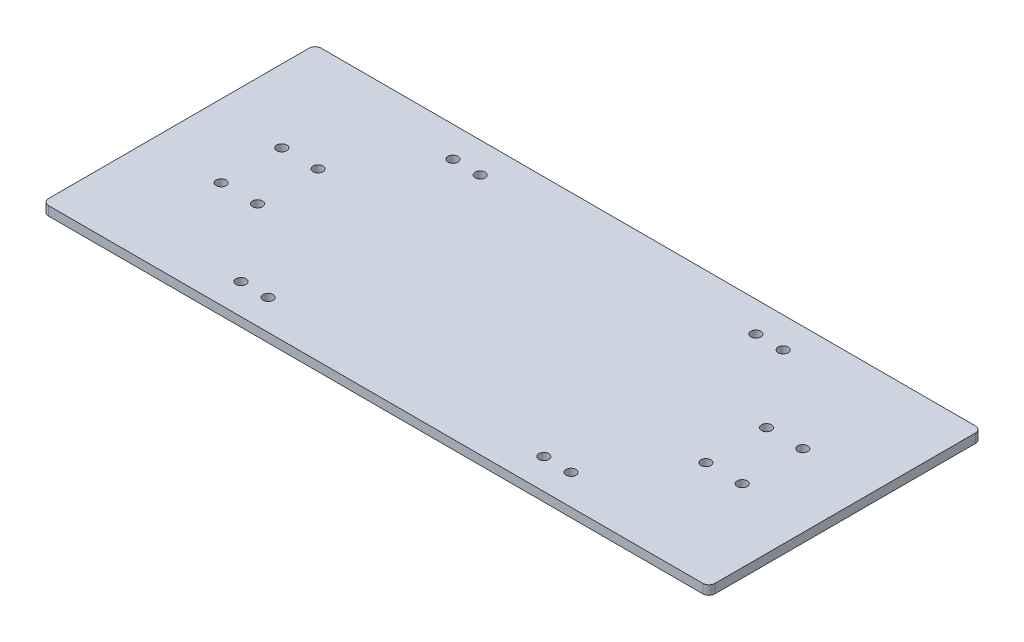
SolidWorks part; units mm, degrees
ref_plane "前视基准面" through (0, 0, 0) normal (0, 0, 1) x (1, 0, 0)
ref_plane "上视基准面" through (0, 0, 0) normal (0, 1, 0) x (1, 0, 0)
ref_plane "右视基准面" through (0, 0, 0) normal (1, 0, 0) x (0, 0, -1)
sketch "草图1" plane through (0, 0, 0) normal (0, 1, 0) x (1, 0, 0)
  line L1 (-110, -45) -> (110, -45)
  line L2 (-110, -45) -> (-110, 45)
  line L3 (-110, 45) -> (110, 45)
  line L4 (110, -45) -> (110, 45)
  line L5 (-110, -45) -> (110, 45) construction
  line L6 (-110, 45) -> (110, -45) construction
  point P0 (0, 0)
  dimension "D1" = 90
  dimension "D2" = 220
extrude "凸台-拉伸1" add sketch "草图1" along normal blind 3
sketch "草图3" plane through (0, 3, 0) normal (0, 1, 0) x (1, 0, 0)
  line L0 (-36.2529, 0) -> (70.3375, 0) construction
  line L1 (23.5, -7.5) -> (43.5, -7.5) construction
  line L2 (23.5, -7.5) -> (23.5, 7.5) construction
  line L3 (23.5, 7.5) -> (43.5, 7.5) construction
  line L4 (43.5, -7.5) -> (43.5, 7.5) construction
  line L5 (23.5, -7.5) -> (43.5, 7.5) construction
  line L6 (23.5, 7.5) -> (43.5, -7.5) construction
  circle A0 centre (43.5, 7.5) radius 1.65
  circle A1 centre (23.5, 7.5) radius 1.65
  circle A2 centre (23.5, -7.5) radius 1.65
  circle A3 centre (43.5, -7.5) radius 1.65
  point P0 (-1.7994, 0)
  point P12 (33.5, 0)
  dimension "D3" = 3.3
  dimension "D4" = 3.3
  dimension "D5" = 3.3
  dimension "D6" = 3.3
  dimension "D1" = 15
  dimension "D2" = 20
  dimension "D7" = 33.5
extrude "切除-拉伸1" [suppressed] cut sketch "草图3" against normal blind 3
sketch "草图4" plane through (0, 3, 0) normal (0, 1, 0) x (1, 0, 0)
  line L0 (0, 51.7691) -> (0, -54.2842) construction
  line L6 (-50, -35) -> (50, -35) construction
  line L7 (-50, -35) -> (-50, 35) construction
  line L8 (-50, 35) -> (50, 35) construction
  line L9 (50, -35) -> (50, 35) construction
  line L10 (-50, -35) -> (50, 35) construction
  line L11 (-50, 35) -> (50, -35) construction
  circle A0 centre (54.5, 35) radius 1.65
  circle A1 centre (45.5, 35) radius 1.65
  circle A3 centre (-54.5, 35) radius 1.65
  circle A4 centre (-45.5, 35) radius 1.65
  point P3 (0, 0)
  dimension "D3" = 3.3
  dimension "D4" = 3.3
  dimension "D5" = 9
  dimension "D6" = 4.5
  dimension "D1" = 100
  dimension "D2" = 70
extrude "切除-拉伸2" cut sketch "草图4" against normal blind 3
mirror "镜向1" about plane through (0, 0, 0) normal (0, 0, 1) of "切除-拉伸2"
mirror "镜向2" [suppressed] about plane through (0, 0, 0) normal (1, 0, 0)
sketch "草图5" plane through (0, 3, 0) normal (0, 1, 0) x (1, 0, 0)
  line L0 (-129.3257, 0) -> (142.7422, 0) construction
  line L1 (0, 64.113) -> (0, -80.8286) construction
  line L3 (74, -10) -> (86, -10) construction
  line L4 (74, -10) -> (74, 10) construction
  line L5 (74, 10) -> (86, 10) construction
  line L6 (86, -10) -> (86, 10) construction
  line L7 (74, -10) -> (86, 10) construction
  line L8 (74, 10) -> (86, -10) construction
  circle A0 centre (86, 10) radius 1.65
  circle A1 centre (74, 10) radius 1.65
  circle A2 centre (74, -10) radius 1.65
  circle A3 centre (86, -10) radius 1.65
  point P5 (80, 0)
  dimension "D4" = 3.3
  dimension "D5" = 3.3
  dimension "D6" = 3.3
  dimension "D7" = 3.3
  dimension "D1" = 20
  dimension "D2" = 12
  dimension "D3" = 80
fillet "圆角1" radius 2 4 edges at (110, 1.5, 45) (-110, 1.5, -45) (110, 1.5, -45) (-110, 1.5, 45)
extrude "切除-拉伸3" cut sketch "草图5" against normal blind 10
mirror "镜向3" about plane through (0, 0, 0) normal (1, 0, 0) of "切除-拉伸3"
